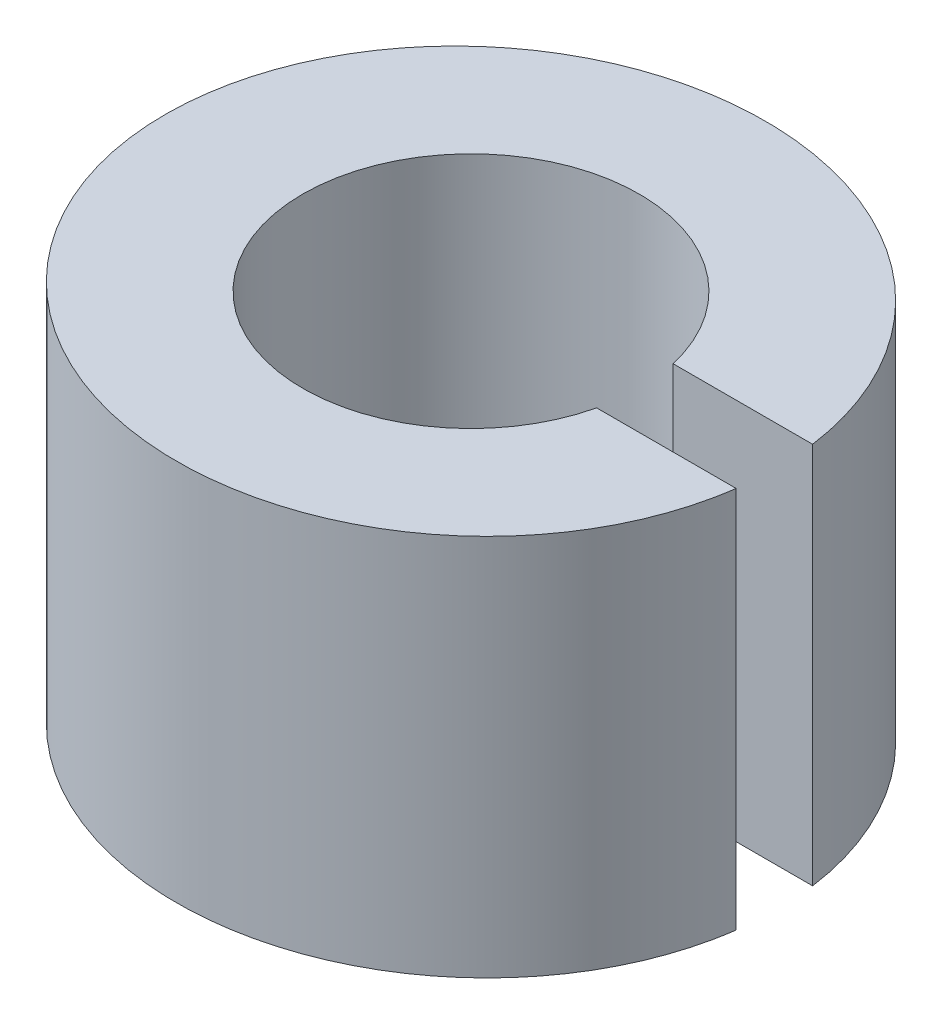
SolidWorks part; units mm, degrees
ref_plane "Front Plane" through (0, 0, 0) normal (0, 0, 1) x (1, 0, 0)
ref_plane "Top Plane" through (0, 0, 0) normal (0, 1, 0) x (1, 0, 0)
ref_plane "Right Plane" through (0, 0, 0) normal (1, 0, 0) x (0, 0, -1)
sketch "Sketch1" plane through (0, 0, 0) normal (0, 1, 0) x (1, 0, 0)
  line L1 (0, 0.635) -> (25.4, 0.635)
  line L2 (0, 0.635) -> (0, -0.635)
  line L3 (0, -0.635) -> (25.4, -0.635)
  line L4 (25.4, 0.635) -> (25.4, -0.635)
  circle A0 centre (0, 0) radius 2.794
  circle A1 centre (0, 0) radius 4.8895 construction
  ellipse E0 centre (0, 0) end of major axis (-5.08, 0) minor radius 4.8895
  point P8 (0, 0)
  dimension "D1" = 5.588
  dimension "D2" = 9.779
  dimension "D3" = 1.27
  dimension "D4" = 25.4
  dimension "D5" = 5.08
extrude "Boss-Extrude1" add sketch "Sketch1" along normal blind 6.35 contours L1 A1 L3 A0
